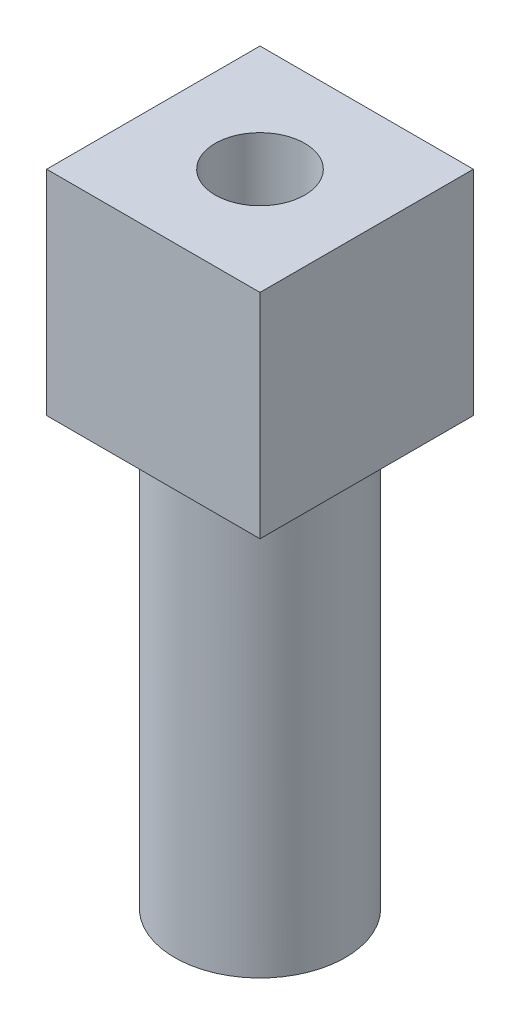
SolidWorks part; units mm, degrees
ref_plane "Ebene vorne" through (0, 0, 0) normal (0, 0, 1) x (1, 0, 0)
ref_plane "Ebene oben" through (0, 0, 0) normal (0, 1, 0) x (1, 0, 0)
ref_plane "Ebene rechts" through (0, 0, 0) normal (1, 0, 0) x (0, 0, -1)
sketch "Skizze1" plane through (0, 0, 0) normal (0, 0, 1) x (1, 0, 0)
  line L0 (0, 0) -> (4, 0)
  line L1 (4, 0) -> (4, 20)
  line L2 (0, 20) -> (4, 20)
  line L4 (0, -2.4593) -> (0, 22.5998) construction
  line L6 (0, 20) -> (0, 0)
  dimension "D1" = 4
  dimension "D2" = 20
revolve "Rotation1" add sketch "Skizze1" angle 360 about L4
sketch "Skizze5" plane through (0, 20, 0) normal (0, 1, 0) x (1, 0, 0)
  line L0 (0, 5) -> (0, -5) construction
  line L1 (-5, 5) -> (5, 5)
  line L2 (-5, 5) -> (-5, -5)
  line L3 (-5, -5) -> (5, -5)
  line L4 (5, 5) -> (5, -5)
  line L5 (5, 0) -> (-5, 0) construction
  dimension "D1" = 10
extrude "Aufsatz-Linear austragen1" add sketch "Skizze5" along normal blind 10
hole_wizard "M5 Gewindebohrung2" positions "Skizze6" profile "Skizze7" tap size "M5" standard "DIN" end condition through all
sketch "Skizze6" plane through (0, 30, 0) normal (0, 1, 0) x (1, 0, 0)
  point P0 (0, 0)
sketch "Skizze7" plane through (0, 30, 0) normal (1, 0, 0) x (0, 0, 1)
  line L0 (0, 0) -> (0, 30)
  line L1 (0, 30) -> (2.1, 30)
  line L2 (2.1, 30) -> (2.1, 0)
  line L5 (2.1, 0) -> (0, 0)
  line L11 (0, -6.35) -> (0, 107.95) construction
  dimension "Bohrerdurchmesser" = 4.2
  dimension "Bohrungstiefe" = 30
cosmetic thread "Bohrungsgewinde2" parameters "D2"=5
